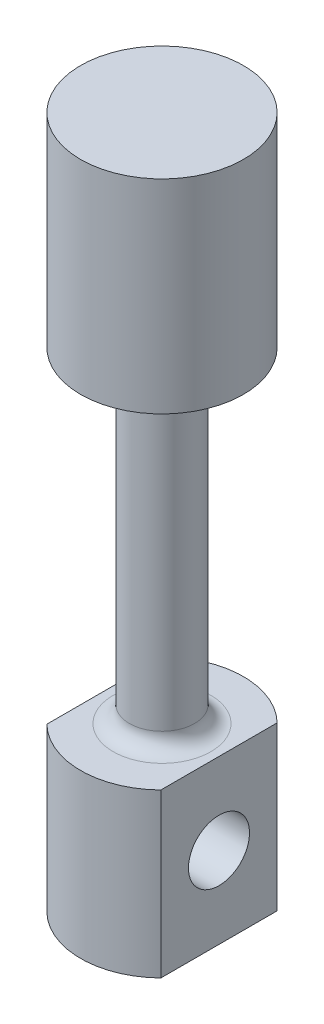
SolidWorks part; units mm, degrees
ref_plane "Front Plane" through (0, 0, 0) normal (0, 0, 1) x (1, 0, 0)
ref_plane "Top Plane" through (0, 0, 0) normal (0, 1, 0) x (1, 0, 0)
ref_plane "Right Plane" through (0, 0, 0) normal (1, 0, 0) x (0, 0, -1)
sketch "Sketch1" plane through (0, 0, 0) normal (0, 1, 0) x (1, 0, 0)
  circle A0 centre (0, 0) radius 6.35
  dimension "D1" = 12.7
extrude "Boss-Extrude1" add sketch "Sketch1" along normal blind 53.975
sketch "Sketch2" plane through (0, 0, 0) normal (0, 0, 1) x (1, 0, 0)
  line L0 (6.35, 53.975) -> (-6.35, 53.975) construction
  line L1 (26.0571, 38.1) -> (3.81, 38.1)
  line L2 (26.0571, 38.1) -> (26.0571, 12.7)
  line L3 (26.0571, 12.7) -> (3.81, 12.7)
  line L4 (2.54, 36.83) -> (2.54, 13.97)
  line L5 (0, 0) -> (0, 53.975) construction
  arc A0 (2.54, 36.83) -> (3.81, 38.1) centre (3.81, 36.83) cw
  arc A1 (2.54, 13.97) -> (3.81, 12.7) centre (3.81, 13.97) ccw
  dimension "D4" = 1.27
  dimension "D1" = 15.875
  dimension "D2" = 25.4
  dimension "D3" = 2.54
revolve "Cut-Revolve1" cut sketch "Sketch2" angle 360 about L5
sketch "Sketch3" plane through (0, 0, 0) normal (0, 0, 1) x (1, 0, 0)
  line L4 (18.2694, 19.3565) -> (4.445, 19.3565)
  line L6 (18.2694, 19.3565) -> (18.2694, -3.6324)
  line L7 (18.2694, -3.6324) -> (4.445, -3.6324)
  line L8 (4.445, 19.3565) -> (4.445, -3.6324)
  dimension "D1" = 4.445
extrude "Cut-Extrude1" cut sketch "Sketch3" against normal through all both and the other way through all
mirror "Mirror1" about plane through (0, 0, 0) normal (1, 0, 0) of "Cut-Extrude1"
hole_wizard "3/16 (0.1875) Diameter Hole1" positions "Sketch5" profile "Sketch6" hole size "3/16" standard "ANSI Inch" end condition through all
sketch "Sketch5" plane through (-4.445, 0, 0) normal (-1, 0, 0) x (0, 0, 1)
  line L1 (-4.5348, 0) -> (4.5348, 0) construction
  point P0 (0, 6.35)
  point P5 (0, 0)
  dimension "D1" = 6.35
sketch "Sketch6" plane through (-4.445, 6.35, 0) normal (0, 1, 0) x (0, 0, 1)
  line L0 (0, 0) -> (0, 10.795)
  line L1 (0, 10.795) -> (2.3812, 10.795)
  line L2 (2.3812, 10.795) -> (2.3812, 0)
  line L5 (2.3812, 0) -> (0, 0)
  line L11 (0, -6.35) -> (0, 107.95) construction
  dimension "Thru Hole Dia." = 4.7625
  dimension "Thru Hole Depth" = 10.795
